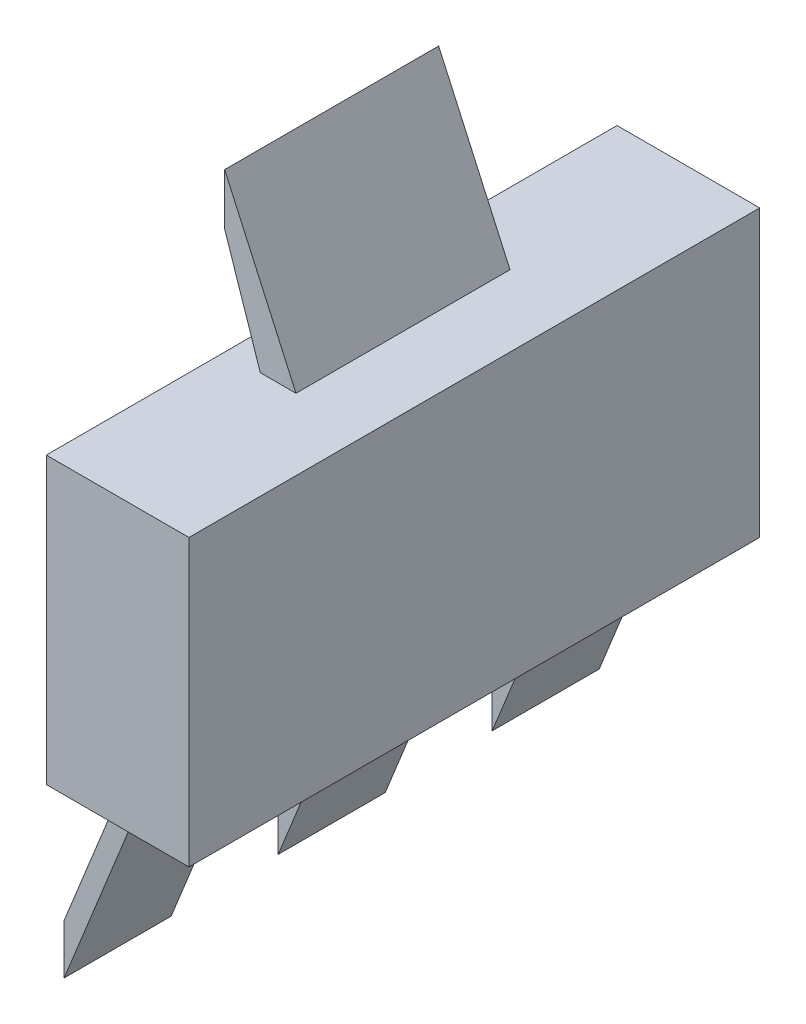
SolidWorks part; units mm, degrees
ref_plane "前视基准面" through (0, 0, 0) normal (0, 0, 1) x (1, 0, 0)
ref_plane "上视基准面" through (0, 0, 0) normal (0, 1, 0) x (1, 0, 0)
ref_plane "右视基准面" through (0, 0, 0) normal (1, 0, 0) x (0, 0, -1)
sketch "草图1" plane through (0, 0, 0) normal (1, 0, 0) x (0, 0, -1)
  line L0 (0, 57.027) -> (0, -37.8081) construction
  line L2 (-4, -2) -> (4, -2)
  line L3 (-4, -2) -> (-4, 2)
  line L4 (-4, 2) -> (4, 2)
  line L5 (4, -2) -> (4, 2)
  line L6 (-4, -2) -> (4, 2) construction
  line L7 (-4, 2) -> (4, -2) construction
  point P3 (0, 0)
  dimension "D1" = 8
  dimension "D2" = 4
extrude "凸台-拉伸1" add sketch "草图1" along normal blind 2
sketch "草图2" plane through (0, 0, 0) normal (0, 0, 1) x (1, 0, 0)
  line L0 (1, 2) -> (0, 4.2154)
  line L1 (2, 2) -> (0, 2) construction
  line L2 (0, 4.2154) -> (0, 3.4933)
  line L3 (0, 3.4933) -> (0.5, 2)
  line L4 (0.5, 2) -> (1, 2)
extrude "凸台-拉伸2" add sketch "草图2" along normal mid plane 3
sketch "草图3" plane through (0, 0, 0) normal (0, 0, 1) x (1, 0, 0)
  line L0 (1, -2) -> (0, -4.4729)
  line L1 (2, -2) -> (0, -2) construction
  line L2 (0, -4.4729) -> (0, -3.7748)
  line L3 (0, -3.7748) -> (0.7177, -2)
  line L4 (0.7177, -2) -> (1, -2)
extrude "凸台-拉伸3" add sketch "草图3" along normal mid plane 1.5
pattern_linear "阵列(线性)1" count 2 spacing 3 along (0, 0, 1) count 2 spacing 3 along (0, 0, -1) of "凸台-拉伸3"
